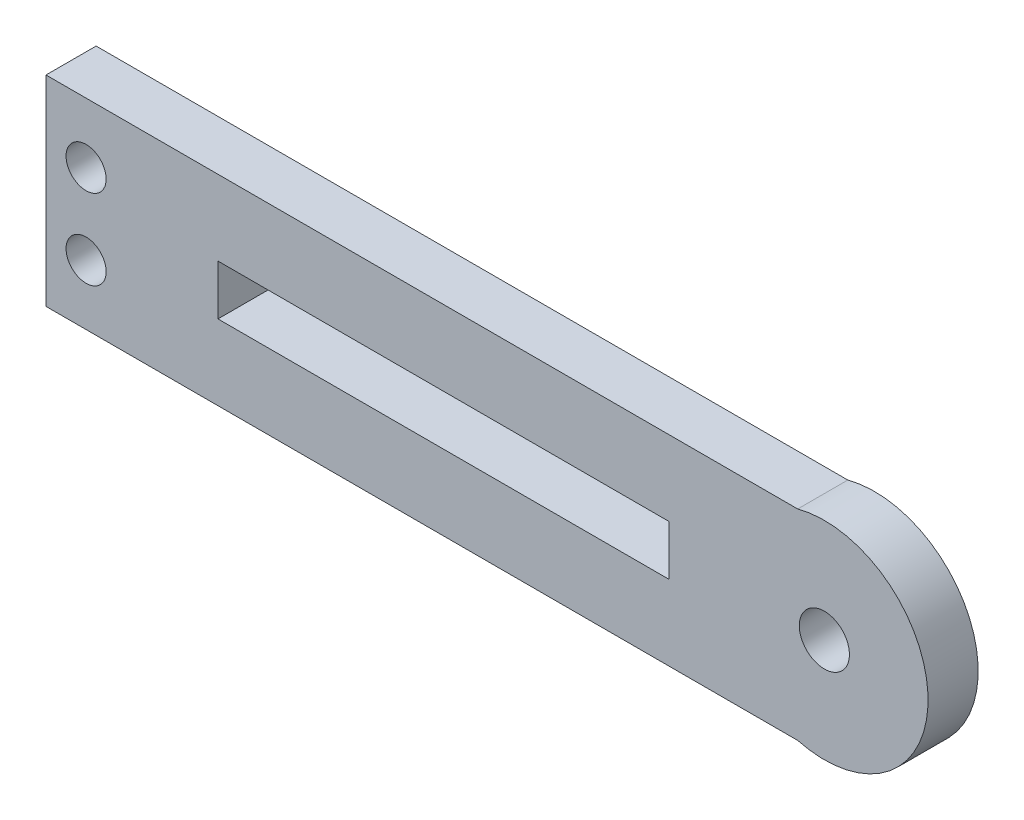
SolidWorks part; units mm, degrees
ref_plane "Piano frontale" through (0, 0, 0) normal (0, 0, 1) x (1, 0, 0)
ref_plane "Piano superiore" through (0, 0, 0) normal (0, 1, 0) x (1, 0, 0)
ref_plane "Piano destro" through (0, 0, 0) normal (1, 0, 0) x (0, 0, -1)
sketch "Schizzo1" plane through (0, 0, 0) normal (0, 0, 1) x (1, 0, 0)
  line L1 (0, -10) -> (75, -10)
  line L2 (0, 10) -> (75, 10)
  line L3 (0, 10) -> (0, -10)
  arc A0 (75, -10) -> (75, 10) centre (77.6603, 0) ccw
  circle A1 centre (77.6603, 0) radius 2.5
  dimension "D2" = 75
  dimension "D1" = 20
  dimension "D3" = 10.3478
  dimension "D4" = 5
extrude "Estrusione-Estrusione1" add sketch "Schizzo1" along normal blind 5
sketch "Schizzo2" plane through (0, 0, 5) normal (0, 0, 1) x (1, 0, 0)
  line L1 (17.1584, -2.5) -> (62.1584, -2.5)
  line L2 (17.1584, -2.5) -> (17.1584, 2.5)
  line L3 (17.1584, 2.5) -> (62.1584, 2.5)
  line L4 (62.1584, -2.5) -> (62.1584, 2.5)
  line L5 (17.1584, -2.5) -> (62.1584, 2.5) construction
  line L6 (17.1584, 2.5) -> (62.1584, -2.5) construction
  line L8 (0, -10) -> (75, -10) construction
  circle A0 centre (77.6603, 0) radius 2.5 construction
  point P0 (39.6584, 0)
  dimension "D1" = 45
  dimension "D2" = 5
  dimension "D3" = 7.5
  dimension "D4" = 15.5019
extrude "Taglio-Estrusione1" cut sketch "Schizzo2" against normal through all
sketch "Schizzo4" plane through (0, 0, 5) normal (0, 0, 1) x (1, 0, 0)
  line L0 (0, 10) -> (0, -10) construction
  line L1 (75, 10) -> (0, 10) construction
  circle A0 centre (4, 4) radius 2
  circle A1 centre (4, -4) radius 2
  dimension "D1" = 4
  dimension "D2" = 4
  dimension "D3" = 8
  dimension "D4" = 4
  dimension "D5" = 6
extrude "Taglio-Estrusione2" cut sketch "Schizzo4" against normal through all
